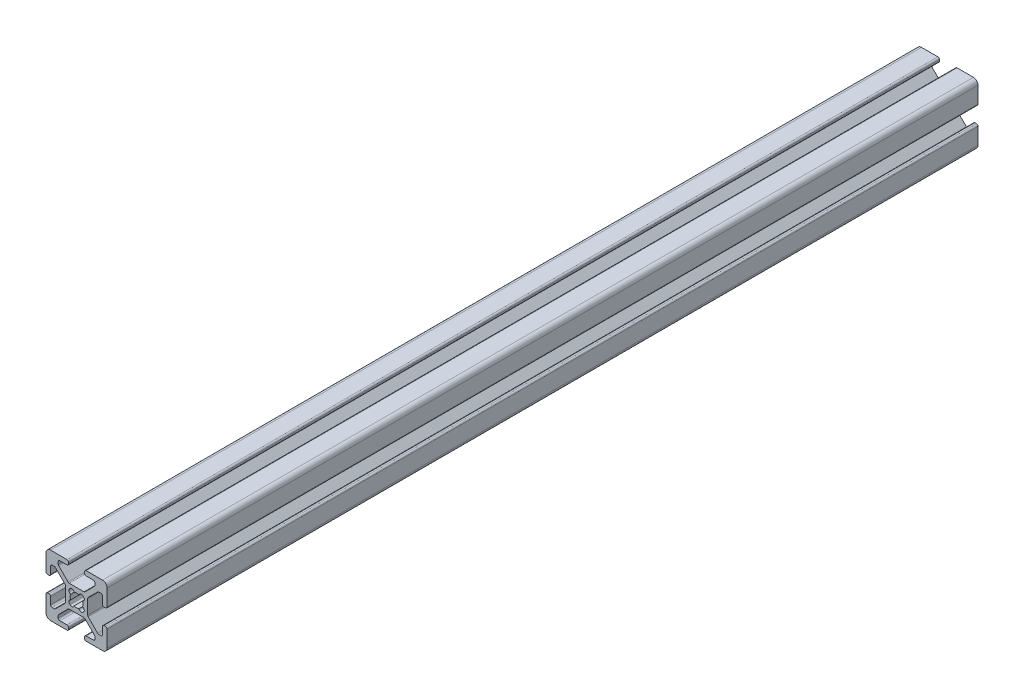
SolidWorks part; units mm, degrees
ref_plane "Front Plane" through (0, 0, 0) normal (0, 0, 1) x (1, 0, 0)
ref_plane "Top Plane" through (0, 0, 0) normal (0, 1, 0) x (1, 0, 0)
ref_plane "Right Plane" through (0, 0, 0) normal (1, 0, 0) x (0, 0, -1)
sketch "Sketch1" plane through (0, 0, 0) normal (0, 0, 1) x (1, 0, 0)
  line L0 (-5.0323, -0.3411) -> (-5.5163, -0.3411)
  line L1 (-6.0243, 0.1669) -> (-6.0243, 2.5159)
  line L2 (-4.5243, 0.1669) -> (-4.5243, 5.5289)
  line L3 (-10.8693, -5.355) -> (-10.8693, -0.5871)
  line L4 (-7.2582, 3.0239) -> (-6.5323, 3.0239)
  line L5 (-7.6174, 2.8752) -> (-10.7205, -0.2279)
  line L6 (-5.0323, -5.6011) -> (-5.5163, -5.6011)
  line L7 (-4.5243, -6.1091) -> (-4.5243, -11.4711)
  line L8 (-6.0243, -6.1091) -> (-6.0243, -8.4581)
  line L9 (-7.2582, -8.9661) -> (-6.5323, -8.9661)
  line L10 (-7.6174, -8.8173) -> (-10.7205, -5.7142)
  line L11 (-12.3994, -5.2756) -> (-12.2198, -5.096)
  line L12 (-17.1543, 6.5209) -> (-17.1543, 6.0369)
  line L13 (-17.6623, 7.0289) -> (-23.0243, 7.0289)
  line L14 (-17.6623, 5.5289) -> (-20.0113, 5.5289)
  line L15 (-12.1404, 0.6839) -> (-16.9082, 0.6839)
  line L16 (-20.5193, 4.295) -> (-20.5193, 5.0209)
  line L17 (-20.3705, 3.9358) -> (-17.2674, 0.8327)
  line L18 (-11.8943, 6.5209) -> (-11.8943, 6.0369)
  line L19 (-11.3863, 7.0289) -> (-6.0243, 7.0289)
  line L20 (-11.3863, 5.5289) -> (-9.0373, 5.5289)
  line L21 (-8.5293, 4.295) -> (-8.5293, 5.0209)
  line L22 (-8.6781, 3.9358) -> (-11.7812, 0.8327)
  line L23 (-12.2198, -0.8462) -> (-12.3994, -0.6666)
  line L24 (-24.0163, -5.6011) -> (-23.5323, -5.6011)
  line L25 (-24.5243, -6.1091) -> (-24.5243, -11.4711)
  line L26 (-23.0243, -6.1091) -> (-23.0243, -8.4581)
  line L27 (-18.1793, -0.5871) -> (-18.1793, -5.355)
  line L28 (-21.7904, -8.9661) -> (-22.5163, -8.9661)
  line L29 (-21.4312, -8.8173) -> (-18.3281, -5.7142)
  line L30 (-24.0163, -0.3411) -> (-23.5323, -0.3411)
  line L31 (-24.5243, 0.1669) -> (-24.5243, 5.5289)
  line L32 (-23.0243, 0.1669) -> (-23.0243, 2.5159)
  line L33 (-21.7904, 3.0239) -> (-22.5163, 3.0239)
  line L34 (-21.4312, 2.8752) -> (-18.3281, -0.2279)
  line L35 (-16.6492, -0.6666) -> (-16.8288, -0.8462)
  line L36 (-11.8943, -12.4631) -> (-11.8943, -11.9791)
  line L37 (-11.3863, -12.9711) -> (-6.0243, -12.9711)
  line L38 (-11.3863, -11.4711) -> (-9.0373, -11.4711)
  line L39 (-16.9082, -6.6261) -> (-12.1404, -6.6261)
  line L40 (-8.5293, -10.2371) -> (-8.5293, -10.9631)
  line L41 (-8.6781, -9.8779) -> (-11.7812, -6.7748)
  line L42 (-17.1543, -12.4631) -> (-17.1543, -11.9791)
  line L43 (-17.6623, -12.9711) -> (-23.0243, -12.9711)
  line L44 (-17.6623, -11.4711) -> (-20.0113, -11.4711)
  line L45 (-20.5193, -10.2371) -> (-20.5193, -10.9631)
  line L46 (-20.3705, -9.8779) -> (-17.2674, -6.7748)
  line L47 (-16.8288, -5.096) -> (-16.6492, -5.2756)
  arc A0 (-15.3283, -4.9062) -> (-13.7203, -4.9062) centre (-14.5243, -2.9711) ccw
  arc A1 (-6.0243, 2.5159) -> (-6.5323, 3.0239) centre (-6.5323, 2.5159) ccw
  arc A2 (-7.2582, 3.0239) -> (-7.6174, 2.8752) centre (-7.2582, 2.5159) ccw
  arc A3 (-10.7205, -0.2279) -> (-10.8693, -0.5871) centre (-10.3613, -0.5871) ccw
  arc A4 (-10.8693, -5.355) -> (-10.7205, -5.7142) centre (-10.3613, -5.355) ccw
  arc A5 (-7.6174, -8.8173) -> (-7.2582, -8.9661) centre (-7.2582, -8.4581) ccw
  arc A6 (-6.5323, -8.9661) -> (-6.0243, -8.4581) centre (-6.5323, -8.4581) ccw
  arc A7 (-5.5163, -5.6011) -> (-6.0243, -6.1091) centre (-5.5163, -6.1091) ccw
  arc A8 (-4.5243, -6.1091) -> (-5.0323, -5.6011) centre (-5.0323, -6.1091) ccw
  arc A9 (-5.0323, -0.3411) -> (-4.5243, 0.1669) centre (-5.0323, 0.1669) ccw
  arc A10 (-6.0243, 0.1669) -> (-5.5163, -0.3411) centre (-5.5163, 0.1669) ccw
  arc A11 (-13.7203, -4.9062) -> (-12.3994, -5.2756) centre (-12.9559, -4.7191) ccw
  arc A12 (-12.2198, -5.096) -> (-12.5892, -3.775) centre (-12.7763, -4.5395) ccw
  arc A13 (-17.1543, 6.5209) -> (-17.6623, 7.0289) centre (-17.6623, 6.5209) ccw
  arc A14 (-17.6623, 5.5289) -> (-17.1543, 6.0369) centre (-17.6623, 6.0369) ccw
  arc A15 (-12.5892, -3.775) -> (-12.5892, -2.1671) centre (-14.5243, -2.9711) ccw
  arc A16 (-17.2674, 0.8327) -> (-16.9082, 0.6839) centre (-16.9082, 1.1919) ccw
  arc A17 (-20.0113, 5.5289) -> (-20.5193, 5.0209) centre (-20.0113, 5.0209) ccw
  arc A18 (-20.5193, 4.295) -> (-20.3705, 3.9358) centre (-20.0113, 4.295) ccw
  arc A19 (-11.8943, 6.0369) -> (-11.3863, 5.5289) centre (-11.3863, 6.0369) ccw
  arc A20 (-11.3863, 7.0289) -> (-11.8943, 6.5209) centre (-11.3863, 6.5209) ccw
  arc A21 (-8.5293, 5.0209) -> (-9.0373, 5.5289) centre (-9.0373, 5.0209) ccw
  arc A22 (-8.6781, 3.9358) -> (-8.5293, 4.295) centre (-9.0373, 4.295) ccw
  arc A23 (-12.1404, 0.6839) -> (-11.7812, 0.8327) centre (-12.1404, 1.1919) ccw
  arc A24 (-12.5892, -2.1671) -> (-12.2198, -0.8462) centre (-12.7763, -1.4027) ccw
  arc A25 (-12.3994, -0.6666) -> (-13.7203, -1.0359) centre (-12.9559, -1.223) ccw
  arc A26 (-24.0163, -5.6011) -> (-24.5243, -6.1091) centre (-24.0163, -6.1091) ccw
  arc A27 (-23.0243, -6.1091) -> (-23.5323, -5.6011) centre (-23.5323, -6.1091) ccw
  arc A28 (-13.7203, -1.0359) -> (-15.3283, -1.0359) centre (-14.5243, -2.9711) ccw
  arc A29 (-18.3281, -5.7142) -> (-18.1793, -5.355) centre (-18.6873, -5.355) ccw
  arc A30 (-23.0243, -8.4581) -> (-22.5163, -8.9661) centre (-22.5163, -8.4581) ccw
  arc A31 (-21.7904, -8.9661) -> (-21.4312, -8.8173) centre (-21.7904, -8.4581) ccw
  arc A32 (-23.5323, -0.3411) -> (-23.0243, 0.1669) centre (-23.5323, 0.1669) ccw
  arc A33 (-24.5243, 0.1669) -> (-24.0163, -0.3411) centre (-24.0163, 0.1669) ccw
  arc A34 (-22.5163, 3.0239) -> (-23.0243, 2.5159) centre (-22.5163, 2.5159) ccw
  arc A35 (-21.4312, 2.8752) -> (-21.7904, 3.0239) centre (-21.7904, 2.5159) ccw
  arc A36 (-18.1793, -0.5871) -> (-18.3281, -0.2279) centre (-18.6873, -0.5871) ccw
  arc A37 (-15.3283, -1.0359) -> (-16.6492, -0.6666) centre (-16.0927, -1.223) ccw
  arc A38 (-16.8288, -0.8462) -> (-16.4594, -2.1671) centre (-16.2723, -1.4027) ccw
  arc A39 (-11.8943, -12.4631) -> (-11.3863, -12.9711) centre (-11.3863, -12.4631) ccw
  arc A40 (-11.3863, -11.4711) -> (-11.8943, -11.9791) centre (-11.3863, -11.9791) ccw
  arc A41 (-16.4594, -2.1671) -> (-16.4594, -3.775) centre (-14.5243, -2.9711) ccw
  arc A42 (-11.7812, -6.7748) -> (-12.1404, -6.6261) centre (-12.1404, -7.1341) ccw
  arc A43 (-9.0373, -11.4711) -> (-8.5293, -10.9631) centre (-9.0373, -10.9631) ccw
  arc A44 (-8.5293, -10.2371) -> (-8.6781, -9.8779) centre (-9.0373, -10.2371) ccw
  arc A45 (-17.1543, -11.9791) -> (-17.6623, -11.4711) centre (-17.6623, -11.9791) ccw
  arc A46 (-17.6623, -12.9711) -> (-17.1543, -12.4631) centre (-17.6623, -12.4631) ccw
  arc A47 (-20.5193, -10.9631) -> (-20.0113, -11.4711) centre (-20.0113, -10.9631) ccw
  arc A48 (-20.3705, -9.8779) -> (-20.5193, -10.2371) centre (-20.0113, -10.2371) ccw
  arc A49 (-16.9082, -6.6261) -> (-17.2674, -6.7748) centre (-16.9082, -7.1341) ccw
  arc A50 (-16.4594, -3.775) -> (-16.8288, -5.096) centre (-16.2723, -4.5395) ccw
  arc A51 (-16.6492, -5.2756) -> (-15.3283, -4.9062) centre (-16.0927, -4.7191) ccw
  arc A52 (-4.5243, 5.5289) -> (-6.0243, 7.0289) centre (-6.0243, 5.5289) ccw
  arc A53 (-6.0243, -12.9711) -> (-4.5243, -11.4711) centre (-6.0243, -11.4711) ccw
  arc A54 (-24.5243, -11.4711) -> (-23.0243, -12.9711) centre (-23.0243, -11.4711) ccw
  arc A55 (-23.0243, 7.0289) -> (-24.5243, 5.5289) centre (-23.0243, 5.5289) ccw
extrude "Extrude1" add sketch "Sketch1" along normal blind 285
